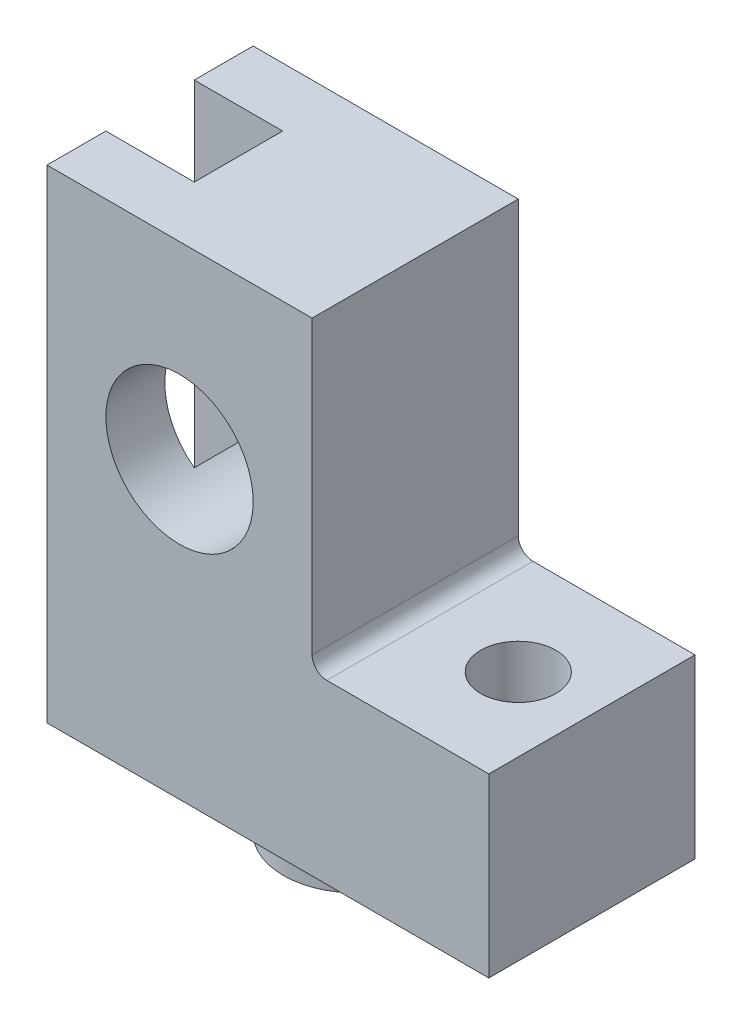
SolidWorks part; units mm, degrees
ref_plane "前视基准面" through (0, 0, 0) normal (0, 0, 1) x (1, 0, 0)
ref_plane "上视基准面" through (0, 0, 0) normal (0, 1, 0) x (1, 0, 0)
ref_plane "右视基准面" through (0, 0, 0) normal (1, 0, 0) x (0, 0, -1)
sketch "草图1" plane through (0, 0, 0) normal (0, 0, 1) x (1, 0, 0)
  line L0 (0, 62.3316) -> (0, -69.8918) construction
  line L1 (-21, 0) -> (21, 0)
  line L2 (21, 0) -> (21, 12)
  line L3 (21, 12) -> (9, 12)
  line L4 (9, 12) -> (9, 32.8)
  line L5 (9, 32.8) -> (-9, 32.8)
  line L6 (-21, 0) -> (-21, 12)
  line L7 (-21, 12) -> (-9, 12)
  line L8 (-9, 12) -> (-9, 32.8)
  circle A0 centre (0, 20) radius 5
  point P9 (0, 0)
  point P12 (0, 32.8)
  dimension "D5" = 10
  dimension "D1" = 32.8
  dimension "D2" = 42
  dimension "D3" = 18
  dimension "D4" = 12
  dimension "D6" = 20
extrude "凸台-拉伸1" add sketch "草图1" along normal mid plane 14
sketch "草图2" plane through (0, 12, 0) normal (0, 1, 0) x (1, 0, 0)
  line L0 (-25.3341, 0) -> (29.8145, 0) construction
  line L1 (0, 10.8063) -> (0, -12.4339) construction
  circle A0 centre (16, 0) radius 2.55
  circle A1 centre (-16, 0) radius 2.55
  dimension "D1" = 5.1
  dimension "D2" = 32
extrude "切除-拉伸1" cut sketch "草图2" against normal through all
sketch "草图4" plane through (0, 32.8, 0) normal (0, 1, 0) x (1, 0, 0)
  line L0 (24.1984, 0) -> (-33.4036, 0) construction
  line L1 (-9, 3) -> (-3, 3)
  line L2 (-9, -7) -> (-9, 7) construction
  line L3 (-9, -3) -> (-3, -3)
  line L4 (-3, 3) -> (-3, -3)
  line L8 (0, -7) -> (0, 7) construction
  line L9 (-9, -3) -> (-9, -7)
  line L10 (-9, -7) -> (-21, -7)
  line L11 (-21, -7) -> (-21, 7)
  line L12 (-21, 7) -> (-9, 7)
  line L13 (-9, 7) -> (-9, 3)
  dimension "D1" = 6
  dimension "D2" = 3
extrude "切除-拉伸2" cut sketch "草图4" against normal through all
fillet "圆角2" radius 1 1 edges at (9, 12, 0)
sketch "草图5" plane through (0, 0, 0) normal (0, -1, 0) x (1, 0, 0)
  circle A0 centre (5, 0) radius 4.95
  dimension "D2" = 9.9
  dimension "D1" = 11
extrude "凸台-拉伸2" add sketch "草图5" along normal blind 3
